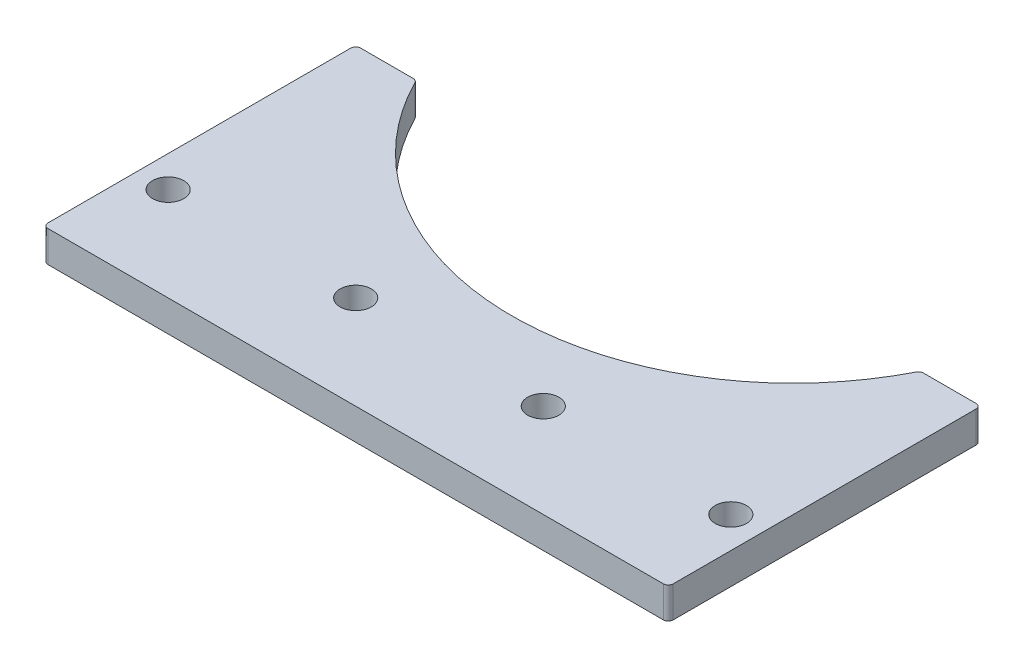
SolidWorks part; units mm, degrees
ref_plane "Front Plane" through (0, 0, 0) normal (0, 0, 1) x (1, 0, 0)
ref_plane "Top Plane" through (0, 0, 0) normal (0, 1, 0) x (1, 0, 0)
ref_plane "Right Plane" through (0, 0, 0) normal (1, 0, 0) x (0, 0, -1)
sketch "Sketch1" plane through (0, 0, 0) normal (0, 1, 0) x (1, 0, 0)
  line L0 (0, 0) -> (0, -88.9) construction
  line L1 (51.1953, -25.4) -> (63.5, -25.4)
  line L2 (-63.5, -88.9) -> (63.5, -88.9)
  line L3 (-63.5, -88.9) -> (-63.5, -25.4)
  line L4 (-63.5, -25.4) -> (-51.1953, -25.4)
  line L5 (63.5, -88.9) -> (63.5, -25.4)
  arc A0 (-51.1953, -25.4) -> (51.1953, -25.4) centre (0, 0) ccw
  dimension "D1" = 114.3
  dimension "D2" = 25.4
  dimension "D3" = 63.5
  dimension "D4" = 127
extrude "Boss-Extrude1" add sketch "Sketch1" along normal blind 6.35
sketch "Sketch2" plane through (0, 6.35, 0) normal (0, 1, 0) x (-1, 0, 0)
  line L0 (63.5, 69.85) -> (-63.5, 69.85) construction
  line L1 (63.5, 25.4) -> (63.5, 88.9) construction
  line L2 (-63.5, 88.9) -> (-63.5, 25.4) construction
  line L3 (0, 69.85) -> (0, 77.9568) construction
  line L4 (63.5, 88.9) -> (-63.5, 88.9) construction
  circle A0 centre (19.05, 69.85) radius 3.175
  circle A1 centre (-19.05, 69.85) radius 3.175
  circle A2 centre (-57.15, 69.85) radius 3.175
  circle A3 centre (57.15, 69.85) radius 3.175
  dimension "D2" = 6.35
  dimension "D4" = 38.1
  dimension "D1" = 19.05
  dimension "D3" = 38.1
extrude "Cut-Extrude1" cut sketch "Sketch2" against normal through all
fillet "Fillet1" radius 1 6 edges at (-51.1953, 3.175, 25.4) (-63.5, 3.175, 25.4) (-63.5, 3.175, 88.9) (63.5, 3.175, 88.9) (51.1953, 3.175, 25.4) (63.5, 3.175, 25.4)
